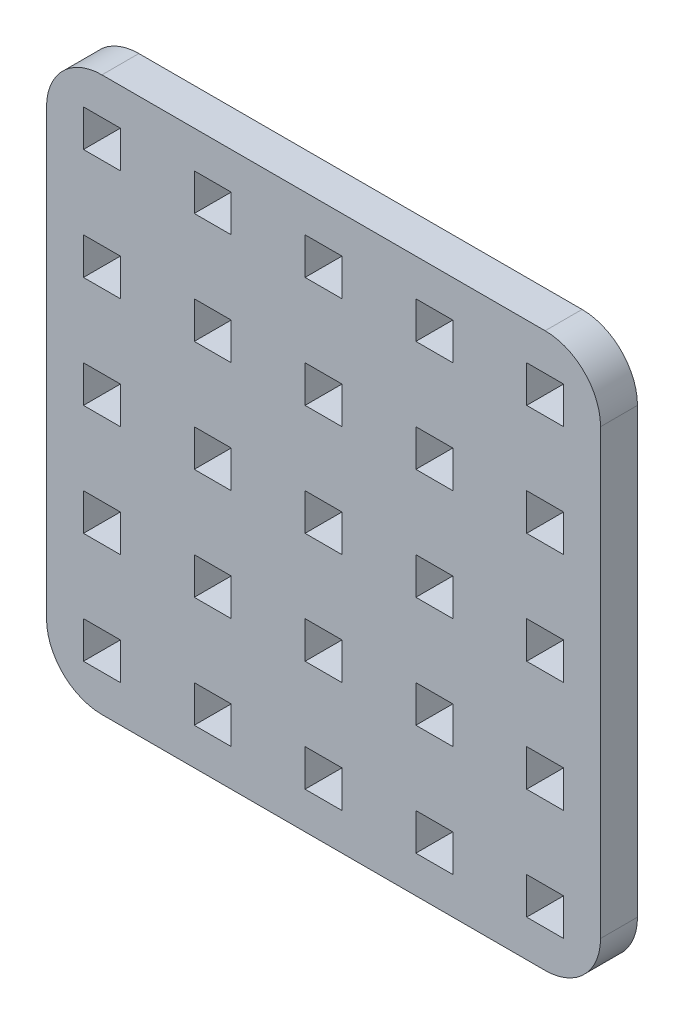
SolidWorks part; units mm, degrees
ref_plane "Alzado" through (0, 0, 0) normal (0, 0, 1) x (1, 0, 0)
ref_plane "Planta" through (0, 0, 0) normal (0, 1, 0) x (1, 0, 0)
ref_plane "Vista lateral" through (0, 0, 0) normal (1, 0, 0) x (0, 0, -1)
sketch "Model" plane through (0, 0, 0) normal (0, 0, 1) x (1, 0, 0)
  line L0 (14.6174, 297.0027) -> (14.6174, 294.0027)
  line L1 (17.6174, 297.0027) -> (14.6174, 297.0027)
  line L2 (17.6174, 294.0027) -> (17.6174, 297.0027)
  line L3 (14.6174, 294.0027) -> (17.6174, 294.0027)
  line L4 (23.6174, 297.0027) -> (23.6174, 294.0027)
  line L5 (26.6174, 297.0027) -> (23.6174, 297.0027)
  line L6 (26.6174, 294.0027) -> (26.6174, 297.0027)
  line L7 (23.6174, 294.0027) -> (26.6174, 294.0027)
  line L8 (32.6174, 297.0027) -> (32.6174, 294.0027)
  line L9 (35.6174, 297.0027) -> (32.6174, 297.0027)
  line L10 (35.6174, 294.0027) -> (35.6174, 297.0027)
  line L11 (32.6174, 294.0027) -> (35.6174, 294.0027)
  line L12 (41.6174, 297.0027) -> (41.6174, 294.0027)
  line L13 (44.6174, 297.0027) -> (41.6174, 297.0027)
  line L14 (44.6174, 294.0027) -> (44.6174, 297.0027)
  line L15 (41.6174, 294.0027) -> (44.6174, 294.0027)
  line L16 (50.6174, 297.0027) -> (50.6174, 294.0027)
  line L17 (53.6174, 297.0027) -> (50.6174, 297.0027)
  line L18 (53.6174, 294.0027) -> (53.6174, 297.0027)
  line L19 (50.6174, 294.0027) -> (53.6174, 294.0027)
  line L20 (14.6174, 261.0027) -> (14.6174, 258.0027)
  line L21 (17.6174, 261.0027) -> (14.6174, 261.0027)
  line L22 (17.6174, 258.0027) -> (17.6174, 261.0027)
  line L23 (14.6174, 258.0027) -> (17.6174, 258.0027)
  line L24 (23.6174, 261.0027) -> (23.6174, 258.0027)
  line L25 (26.6174, 261.0027) -> (23.6174, 261.0027)
  line L26 (26.6174, 258.0027) -> (26.6174, 261.0027)
  line L27 (23.6174, 258.0027) -> (26.6174, 258.0027)
  line L28 (32.6174, 261.0027) -> (32.6174, 258.0027)
  line L29 (35.6174, 261.0027) -> (32.6174, 261.0027)
  line L30 (35.6174, 258.0027) -> (35.6174, 261.0027)
  line L31 (32.6174, 258.0027) -> (35.6174, 258.0027)
  line L32 (41.6174, 261.0027) -> (41.6174, 258.0027)
  line L33 (44.6174, 261.0027) -> (41.6174, 261.0027)
  line L34 (44.6174, 258.0027) -> (44.6174, 261.0027)
  line L35 (41.6174, 258.0027) -> (44.6174, 258.0027)
  line L36 (50.6174, 261.0027) -> (50.6174, 258.0027)
  line L37 (53.6174, 261.0027) -> (50.6174, 261.0027)
  line L38 (53.6174, 258.0027) -> (53.6174, 261.0027)
  line L39 (50.6174, 258.0027) -> (53.6174, 258.0027)
  line L40 (14.6174, 288.0027) -> (14.6174, 285.0027)
  line L41 (17.6174, 288.0027) -> (14.6174, 288.0027)
  line L42 (17.6174, 285.0027) -> (17.6174, 288.0027)
  line L43 (14.6174, 285.0027) -> (17.6174, 285.0027)
  line L44 (23.6174, 288.0027) -> (23.6174, 285.0027)
  line L45 (26.6174, 288.0027) -> (23.6174, 288.0027)
  line L46 (26.6174, 285.0027) -> (26.6174, 288.0027)
  line L47 (23.6174, 285.0027) -> (26.6174, 285.0027)
  line L48 (32.6174, 288.0027) -> (32.6174, 285.0027)
  line L49 (35.6174, 288.0027) -> (32.6174, 288.0027)
  line L50 (35.6174, 285.0027) -> (35.6174, 288.0027)
  line L51 (32.6174, 285.0027) -> (35.6174, 285.0027)
  line L52 (41.6174, 288.0027) -> (41.6174, 285.0027)
  line L53 (44.6174, 288.0027) -> (41.6174, 288.0027)
  line L54 (44.6174, 285.0027) -> (44.6174, 288.0027)
  line L55 (41.6174, 285.0027) -> (44.6174, 285.0027)
  line L56 (50.6174, 288.0027) -> (50.6174, 285.0027)
  line L57 (53.6174, 288.0027) -> (50.6174, 288.0027)
  line L58 (53.6174, 285.0027) -> (53.6174, 288.0027)
  line L59 (50.6174, 285.0027) -> (53.6174, 285.0027)
  line L60 (14.6174, 279.0027) -> (14.6174, 276.0027)
  line L61 (17.6174, 279.0027) -> (14.6174, 279.0027)
  line L62 (17.6174, 276.0027) -> (17.6174, 279.0027)
  line L63 (14.6174, 276.0027) -> (17.6174, 276.0027)
  line L64 (23.6174, 279.0027) -> (23.6174, 276.0027)
  line L65 (26.6174, 279.0027) -> (23.6174, 279.0027)
  line L66 (26.6174, 276.0027) -> (26.6174, 279.0027)
  line L67 (23.6174, 276.0027) -> (26.6174, 276.0027)
  line L68 (32.6174, 279.0027) -> (32.6174, 276.0027)
  line L69 (35.6174, 279.0027) -> (32.6174, 279.0027)
  line L70 (35.6174, 276.0027) -> (35.6174, 279.0027)
  line L71 (32.6174, 276.0027) -> (35.6174, 276.0027)
  line L72 (41.6174, 279.0027) -> (41.6174, 276.0027)
  line L73 (44.6174, 279.0027) -> (41.6174, 279.0027)
  line L74 (44.6174, 276.0027) -> (44.6174, 279.0027)
  line L75 (41.6174, 276.0027) -> (44.6174, 276.0027)
  line L76 (50.6174, 279.0027) -> (50.6174, 276.0027)
  line L77 (53.6174, 279.0027) -> (50.6174, 279.0027)
  line L78 (53.6174, 276.0027) -> (53.6174, 279.0027)
  line L79 (50.6174, 276.0027) -> (53.6174, 276.0027)
  line L80 (14.6174, 270.0027) -> (14.6174, 267.0027)
  line L81 (17.6174, 270.0027) -> (14.6174, 270.0027)
  line L82 (17.6174, 267.0027) -> (17.6174, 270.0027)
  line L83 (14.6174, 267.0027) -> (17.6174, 267.0027)
  line L84 (23.6174, 270.0027) -> (23.6174, 267.0027)
  line L85 (26.6174, 270.0027) -> (23.6174, 270.0027)
  line L86 (26.6174, 267.0027) -> (26.6174, 270.0027)
  line L87 (23.6174, 267.0027) -> (26.6174, 267.0027)
  line L88 (32.6174, 270.0027) -> (32.6174, 267.0027)
  line L89 (35.6174, 270.0027) -> (32.6174, 270.0027)
  line L90 (35.6174, 267.0027) -> (35.6174, 270.0027)
  line L91 (32.6174, 267.0027) -> (35.6174, 267.0027)
  line L92 (41.6174, 270.0027) -> (41.6174, 267.0027)
  line L93 (44.6174, 270.0027) -> (41.6174, 270.0027)
  line L94 (44.6174, 267.0027) -> (44.6174, 270.0027)
  line L95 (41.6174, 267.0027) -> (44.6174, 267.0027)
  line L96 (50.6174, 270.0027) -> (50.6174, 267.0027)
  line L97 (53.6174, 270.0027) -> (50.6174, 270.0027)
  line L98 (53.6174, 267.0027) -> (53.6174, 270.0027)
  line L99 (50.6174, 267.0027) -> (53.6174, 267.0027)
  line L100 (16.1174, 300.0027) -> (52.1174, 300.0027)
  line L101 (16.1174, 255.0027) -> (52.1174, 255.0027)
  line L102 (11.6174, 295.5027) -> (11.6174, 259.5027)
  line L103 (56.6174, 295.5027) -> (56.6174, 259.5027)
  arc A0 (56.6174, 295.5027) -> (52.1174, 300.0027) centre (52.1174, 295.5027) ccw
  arc A1 (52.1174, 255.0027) -> (56.6174, 259.5027) centre (52.1174, 259.5027) ccw
  arc A2 (16.1174, 300.0027) -> (11.6174, 295.5027) centre (16.1174, 295.5027) ccw
  arc A3 (11.6174, 259.5027) -> (16.1174, 255.0027) centre (16.1174, 259.5027) ccw
extrude "Saliente-Extruir1" add sketch "Model" along normal blind 3
